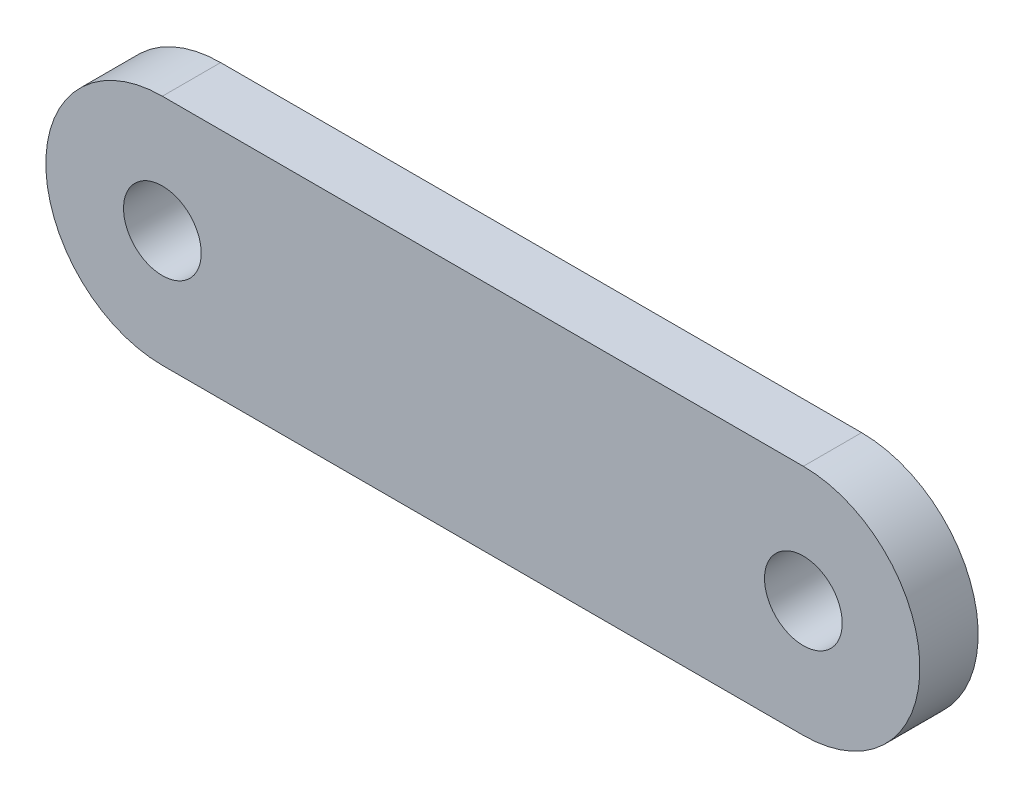
SolidWorks part; units mm, degrees
ref_plane "前视基准面" through (0, 0, 0) normal (0, 0, 1) x (1, 0, 0)
ref_plane "上视基准面" through (0, 0, 0) normal (0, 1, 0) x (1, 0, 0)
ref_plane "右视基准面" through (0, 0, 0) normal (1, 0, 0) x (0, 0, -1)
sketch "草图1" plane through (0, 0, 0) normal (0, 0, 1) x (1, 0, 0)
  line L0 (-497.1836, 0) -> (24361.9946, 0) construction
  line L1 (0, -6) -> (33, -6)
  line L2 (0, 6) -> (33, 6)
  circle A0 centre (0, 0) radius 2
  circle A1 centre (0, 0) radius 6
  circle A2 centre (33, 0) radius 2
  circle A3 centre (33, 0) radius 6
  dimension "D1" = 12
  dimension "D2" = 4
  dimension "D4" = 33
  dimension "D3" = 2
extrude "凸台-拉伸1" add sketch "草图1" along normal blind 3 contours A1 L0 A3 L2 | L0 A1 L1 A3 | L0 A1 A0 | A1 L0 A0 | A3 L0 A2 | L0 A3 A2
